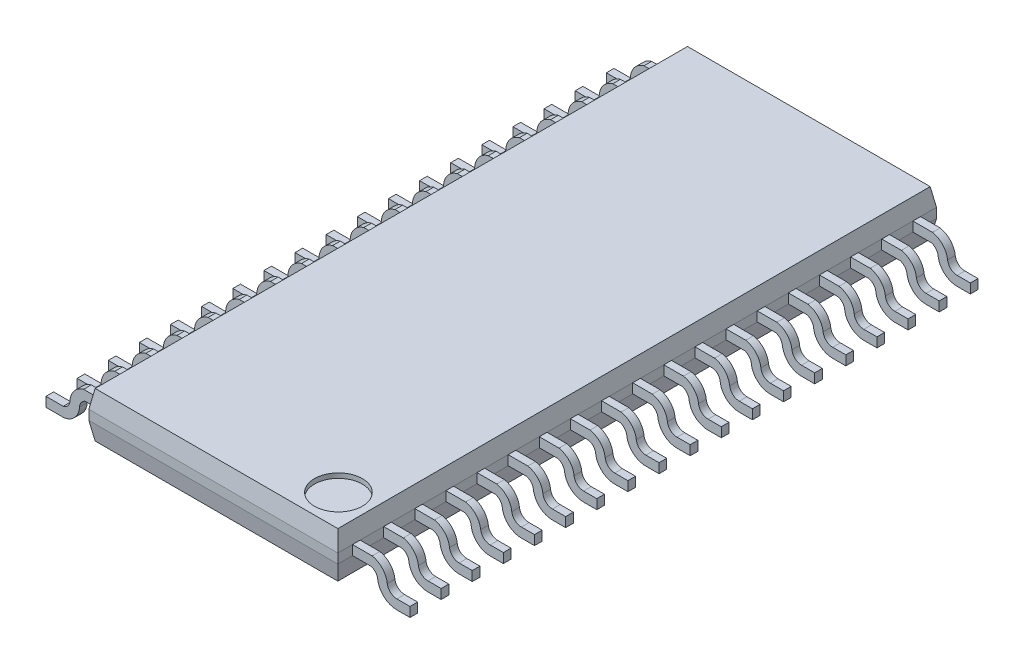
SolidWorks part; units mm, degrees
ref_plane "Front Plane" through (0, 0, 0) normal (0, 0, 1) x (1, 0, 0)
ref_plane "Top Plane" through (0, 0, 0) normal (0, 1, 0) x (1, 0, 0)
ref_plane "Right Plane" through (0, 0, 0) normal (1, 0, 0) x (0, 0, -1)
sketch "Sketch1" plane through (0, 0, 0) normal (0, 0, 1) x (1, 0, 0)
  line L0 (0, 0) -> (0, 10.0919) construction
  line L1 (3, 0) -> (-3, 0)
  line L4 (-3.4295, -0.52) -> (-3.8, -0.52)
  line L5 (3.5256, -0.52) -> (3.8, -0.52)
  line L6 (-2.8, 0) -> (-2.8, 1.3793) construction
  line L7 (2.4, 0) -> (2.4, 1.3793) construction
  arc A0 (-3.4295, -0.52) -> (-3.1995, -0.2596) centre (-3.4801, -0.2435) ccw
  arc A1 (-3.1995, -0.2596) -> (-3, 0) centre (-2.9091, -0.2763) cw
  arc A2 (3.5256, -0.52) -> (3.2262, -0.2535) centre (3.5256, -0.2186) cw
  arc A3 (3, 0) -> (3.2262, -0.2535) centre (2.9328, -0.2877) cw
  dimension "D5" = 0
  dimension "D6" = 0.6005
  dimension "D1" = 1
  dimension "D2" = 0
  dimension "D3" = 0.52
  dimension "D4" = 6
  dimension "D7" = 2.8
  dimension "D8" = 5.2
extrude "Extrude-Thin1" add sketch "Sketch1" along normal mid plane 0.16 thin thin type mid plane wall 0.2
pattern_linear "LPattern2" count 19 spacing 0.65 along (0, 0, -1) of "Extrude-Thin1"
sketch "Sketch16" plane through (0, 0, 0) normal (0, 1, 0) x (1, 0, 0)
  line L0 (0, 0.7616) -> (0, 10.9662) construction
  line L4 (-2.6, -0.3861) -> (2.6, -0.3861)
  line L5 (-2.6, -0.3861) -> (-2.6, 12.1139)
  line L6 (-2.6, 12.1139) -> (2.6, 12.1139)
  line L7 (2.6, -0.3861) -> (2.6, 12.1139)
  line L8 (-2.6, -0.3861) -> (2.6, 12.1139) construction
  line L9 (-2.6, 12.1139) -> (2.6, -0.3861) construction
  point P6 (0, 5.8639)
  dimension "D1" = 12.5
  dimension "D2" = 5.2
extrude "Boss-Extrude1" add sketch "Sketch16" along normal mid plane 0.201
sketch "Sketch17" plane through (0, 0.1005, 0) normal (0, 1, 0) x (1, 0, 0)
  line L4 (2.6, -0.3861) -> (2.6, 12.1139)
  line L5 (2.6, 12.1139) -> (-2.6, 12.1139)
  line L6 (-2.6, 12.1139) -> (-2.6, -0.3861)
  line L7 (-2.6, -0.3861) -> (2.6, -0.3861)
  line L8 (2.6, -0.3861) -> (2.6, 12.1139)
  line L9 (2.6, 12.1139) -> (-2.6, 12.1139)
  line L10 (-2.6, 12.1139) -> (-2.6, -0.3861)
  line L11 (-2.6, -0.3861) -> (2.6, -0.3861)
  dimension "D1" = 0
extrude "Boss-Extrude2" add sketch "Sketch17" along normal blind 0.375 draft 10
mirror "Mirror1" about plane through (0, 0, 0) normal (0, 1, 0) of "Boss-Extrude2"
sketch "Sketch18" plane through (0, 0.4755, 0) normal (0, 1, 0) x (1, 0, 0)
  line L0 (0, -0.32) -> (0, 12.0478) construction
  line L1 (-2.5339, -0.32) -> (2.5339, -0.32) construction
  line L2 (2.5339, 12.0478) -> (-2.5339, 12.0478) construction
  line L3 (2.5339, 5.8639) -> (-2.5339, 5.8639) construction
  line L4 (2.5339, -0.32) -> (2.5339, 12.0478) construction
  line L5 (-2.5339, 12.0478) -> (-2.5339, -0.32) construction
  circle A0 centre (1.8855, 0.3401) radius 0.5
extrude "Cut-Extrude1" cut sketch "Sketch18" against normal blind 0.1
sketch "Sketch19" plane through (0, -0.4755, 0) normal (0, -1, 0) x (1, 0, 0)
  line L0 (0, 0.32) -> (0, -12.0478) construction
  line L1 (-2.5339, 0.32) -> (2.5339, 0.32) construction
  line L2 (2.5339, -12.0478) -> (-2.5339, -12.0478) construction
  line L3 (-2.5339, -5.8639) -> (2.5339, -5.8639) construction
  line L4 (-2.5339, -12.0478) -> (-2.5339, 0.32) construction
  line L5 (2.5339, 0.32) -> (2.5339, -12.0478) construction
  line L7 (-1.695, -9.0389) -> (1.695, -9.0389)
  line L8 (-1.695, -9.0389) -> (-1.695, -2.6889)
  line L9 (-1.695, -2.6889) -> (1.695, -2.6889)
  line L10 (1.695, -9.0389) -> (1.695, -2.6889)
  line L11 (-1.695, -9.0389) -> (1.695, -2.6889) construction
  line L12 (-1.695, -2.6889) -> (1.695, -9.0389) construction
  point P14 (0, -5.8639)
  dimension "D3" = 3.39
  dimension "D4" = 6.35
extrude "Cut-Extrude2" cut sketch "Sketch19" against normal blind 0.1
